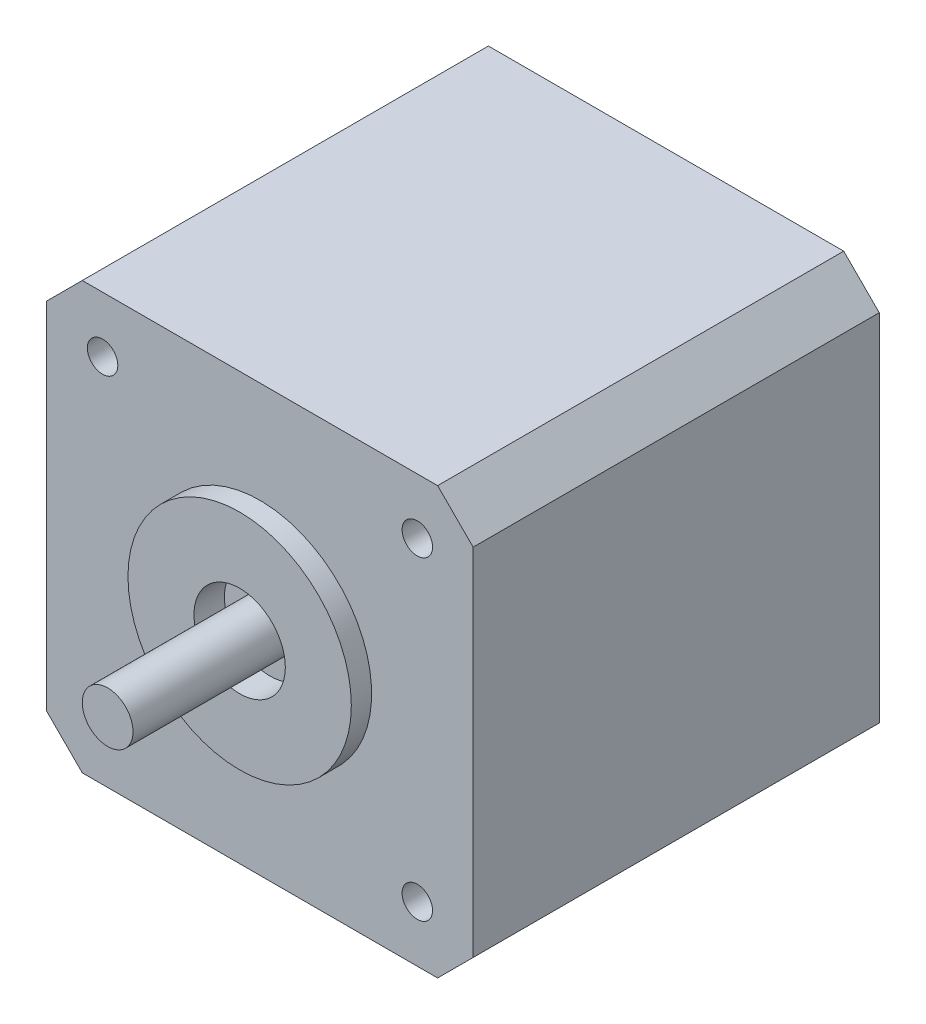
SolidWorks part; units mm, degrees
ref_plane "Front Plane" through (0, 0, 0) normal (0, 0, 1) x (1, 0, 0)
ref_plane "Top Plane" through (0, 0, 0) normal (0, 1, 0) x (1, 0, 0)
ref_plane "Right Plane" through (0, 0, 0) normal (1, 0, 0) x (0, 0, -1)
sketch "Sketch1" plane through (0, 0, 0) normal (0, 0, 1) x (1, 0, 0)
  line L1 (-21, -21) -> (21, -21)
  line L2 (-21, -21) -> (-21, 21)
  line L3 (-21, 21) -> (21, 21)
  line L4 (21, -21) -> (21, 21)
  line L5 (-21, -21) -> (21, 21) construction
  line L6 (-21, 21) -> (21, -21) construction
  point P0 (0, 0)
  dimension "D1" = 42
extrude "Boss-Extrude1" add sketch "Sketch1" against normal blind 40
chamfer "Chamfer1" distance 3.5 angle 45 4 edges at (-21, -21, -20) (21, -21, -20) (-21, 21, -20) (21, 21, -20)
sketch "Sketch2" plane through (0, 0, 0) normal (0, 0, 1) x (1, 0, 0)
  circle A0 centre (0, 0) radius 11
  dimension "D1" = 22
extrude "Boss-Extrude2" add sketch "Sketch2" along normal blind 2
sketch "Sketch3" plane through (0, 0, 0) normal (0, 0, 1) x (1, 0, 0)
  line L0 (0, 0) -> (15.5, 15.5) construction
  line L1 (0, 0) -> (-15.5, 15.5) construction
  line L3 (21, 17.5) -> (17.5, 21) construction
  circle A0 centre (15.5, 15.5) radius 1.5
  circle A1 centre (-15.5, 15.5) radius 1.5
  circle A2 centre (-15.5, -15.5) radius 1.5
  circle A3 centre (15.5, -15.5) radius 1.5
  dimension "D1" = 3
  dimension "D2" = 31
  dimension "D3" = 27.2236
extrude "Cut-Extrude1" cut sketch "Sketch3" against normal through all
sketch "Sketch4" plane through (0, 0, 2) normal (0, 0, 1) x (1, 0, 0)
  circle A0 centre (0, 0) radius 2.5
  dimension "D1" = 5
extrude "Boss-Extrude3" add sketch "Sketch4" along normal blind 13
sketch "Sketch5" plane through (0, 0, -40) normal (0, 0, -1) x (-1, 0, 0)
  circle A0 centre (0, 0) radius 2.5
  dimension "D1" = 5
extrude "Boss-Extrude4" add sketch "Sketch5" along normal blind 15
sketch "Sketch6" plane through (0, 0, 0) normal (0, 0, 1) x (1, 0, 0)
  circle A0 centre (-15.5, 15.5) radius 3
  circle A1 centre (15.5, 15.5) radius 3
  circle A2 centre (15.5, -15.5) radius 3
  circle A3 centre (-15.5, -15.5) radius 3
  dimension "D1" = 6
sketch "Sketch7" plane through (0, 0, 0) normal (0, 1, 0) x (1, 0, 0)
  line L0 (0, -1000) -> (0, 49000) construction
sketch "Sketch8" plane through (0, 0, 2) normal (0, 0, 1) x (1, 0, 0)
  circle A0 centre (0, 0) radius 4.5
  circle A1 centre (0, 0) radius 2.5
  circle A2 centre (0, 0) radius 2.5 construction
  dimension "D1" = 9
extrude "Cut-Extrude2" cut sketch "Sketch8" against normal blind 3
